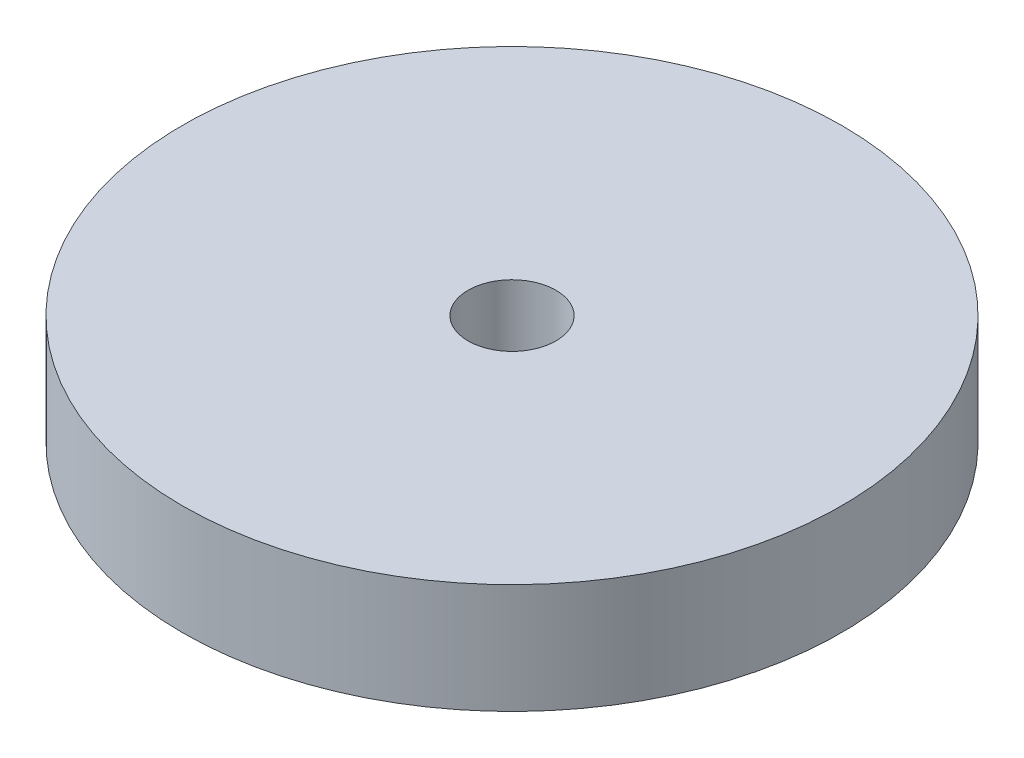
SolidWorks part; units mm, degrees
ref_plane "前视基准面" through (0, 0, 0) normal (0, 0, 1) x (1, 0, 0)
ref_plane "上视基准面" through (0, 0, 0) normal (0, 1, 0) x (1, 0, 0)
ref_plane "右视基准面" through (0, 0, 0) normal (1, 0, 0) x (0, 0, -1)
other "Configuration Table"
sketch "草图1" plane through (0, 0, 0) normal (0, 1, 0) x (1, 0, 0)
  circle A0 centre (0, 0) radius 2
  circle A1 centre (0, 0) radius 15
  dimension "D1" = 30
  dimension "D2" = 4
extrude "凸台-拉伸1" add sketch "草图1" along normal blind 5
